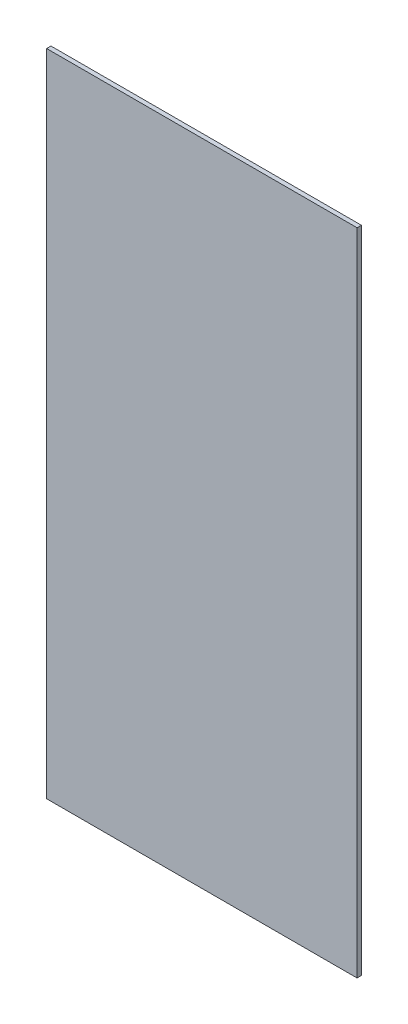
SolidWorks part; units mm, degrees
ref_plane "前视基准面" through (0, 0, 0) normal (0, 0, 1) x (1, 0, 0)
ref_plane "上视基准面" through (0, 0, 0) normal (0, 1, 0) x (1, 0, 0)
ref_plane "右视基准面" through (0, 0, 0) normal (1, 0, 0) x (0, 0, -1)
sketch "草图2" plane through (0, 0, 0) normal (0, 0, 1) x (1, 0, 0)
  line L1 (-107.5, -225) -> (107.5, -225)
  line L2 (-107.5, -225) -> (-107.5, 225)
  line L3 (-107.5, 225) -> (107.5, 225)
  line L4 (107.5, -225) -> (107.5, 225)
  line L5 (-107.5, -225) -> (107.5, 225) construction
  line L6 (-107.5, 225) -> (107.5, -225) construction
  point P0 (0, 0)
  dimension "D1" = 215
  dimension "D2" = 450
extrude "凸台-拉伸1" add sketch "草图2" along normal blind 3
